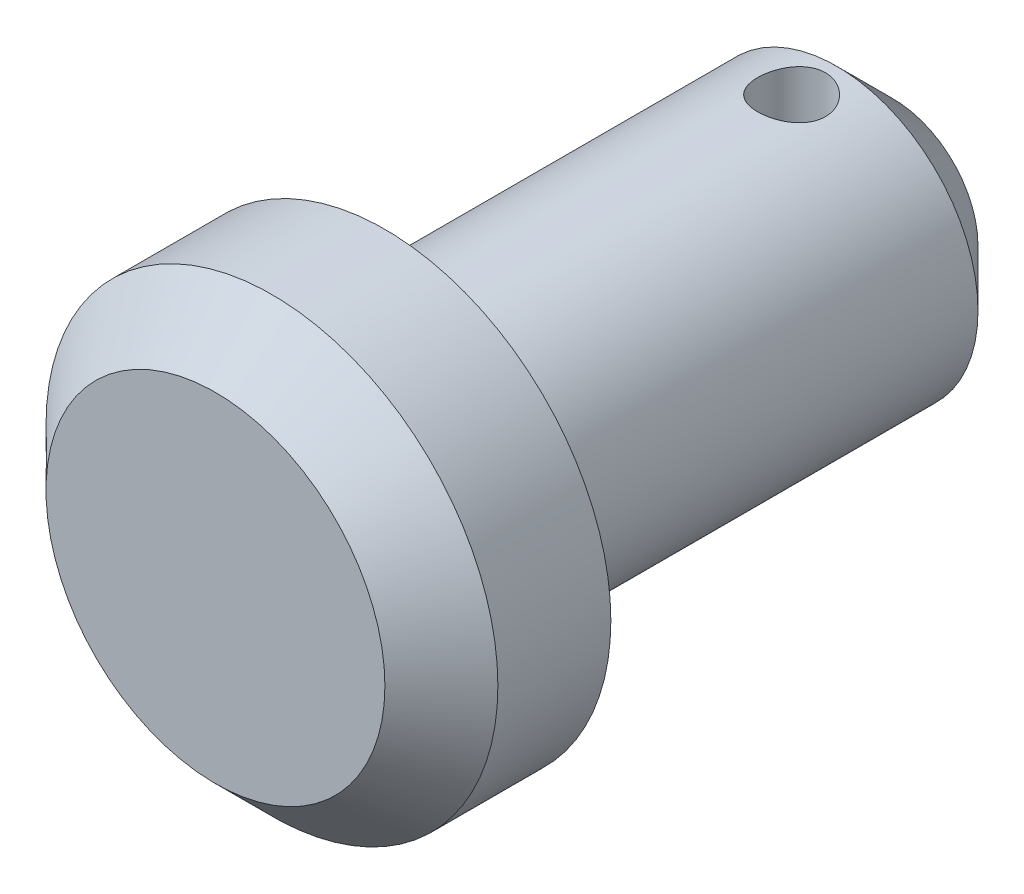
SolidWorks part; units mm, degrees
ref_plane "Front Plane" through (0, 0, 0) normal (0, 0, 1) x (1, 0, 0)
ref_plane "Top Plane" through (0, 0, 0) normal (0, 1, 0) x (1, 0, 0)
ref_plane "Right Plane" through (0, 0, 0) normal (1, 0, 0) x (0, 0, -1)
sketch "Sketch1" plane through (0, 0, 0) normal (1, 0, 0) x (0, 0, -1)
  line L0 (0, 0) -> (120, 0)
  line L1 (0, 0) -> (0, 30)
  line L2 (10, 40) -> (30, 40)
  line L3 (0, 30) -> (10, 40)
  line L4 (30, 40) -> (30, 25)
  line L5 (30, 25) -> (110, 25)
  line L6 (120, 0) -> (120, 15)
  line L7 (120, 15) -> (110, 25)
  point P4 (0, 40)
  point P7 (0, 0)
  dimension "D1" = 120
  dimension "D2" = 40
  dimension "D3" = 30
  dimension "D4" = 10
  dimension "D5" = 45
  dimension "D6" = 25
  dimension "D7" = 15
revolve "Revolve1" add sketch "Sketch1" angle 360 about L0
sketch "Sketch2" plane through (0, 0, 0) normal (0, 1, 0) x (1, 0, 0)
  line L0 (0, 30) -> (0, 102) construction
  line L1 (40, 30) -> (-40, 30) construction
  circle A0 centre (0, 102) radius 6
  dimension "D2" = 12
  dimension "D1" = 72
extrude "Cut-Extrude1" cut sketch "Sketch2" against normal through all and the other way through all
